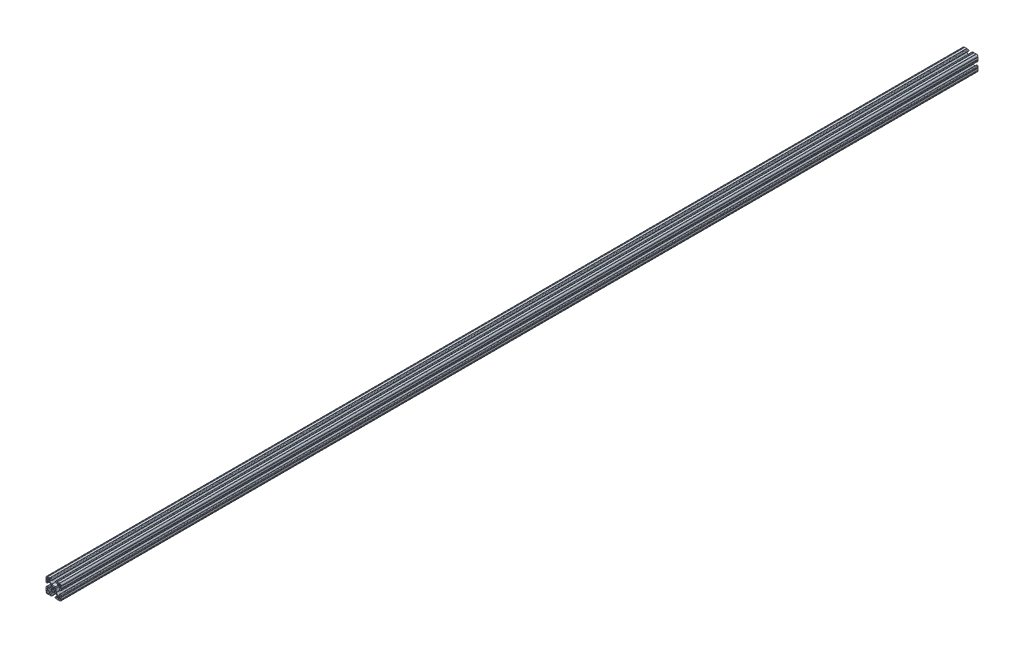
SolidWorks part; units mm, degrees
ref_plane "Front Plane" through (0, 0, 0) normal (0, 0, 1) x (1, 0, 0)
ref_plane "Top Plane" through (0, 0, 0) normal (0, 1, 0) x (1, 0, 0)
ref_plane "Right Plane" through (0, 0, 0) normal (1, 0, 0) x (0, 0, -1)
ref_plane "Plane1" through (0, 0, -2322.576) normal (0, 0, -1) x (-1, 0, 0)
sketch "Sketch1" plane through (0, 0, -2322.576) normal (0, 0, -1) x (-1, 0, 0)
  line L0 (17.2466, 14.4526) -> (17.2466, 12.2428)
  line L1 (16.8656, 11.8618) -> (15.0927, 11.8618)
  line L2 (15.0927, 11.8618) -> (14.5542, 12.4003)
  line L3 (14.5542, 12.4003) -> (14.0157, 11.8618)
  line L4 (14.0157, 11.8618) -> (12.2428, 11.8618)
  line L5 (11.8618, 12.2428) -> (11.8618, 14.0157)
  line L6 (11.8618, 14.0157) -> (12.4003, 14.5542)
  line L7 (12.4003, 14.5542) -> (11.8618, 15.0927)
  line L8 (11.8618, 15.0927) -> (11.8618, 16.8656)
  line L9 (12.2428, 17.2466) -> (14.4526, 17.2466)
  line L10 (17.2466, -12.2428) -> (17.2466, -14.4526)
  line L11 (14.4526, -17.2466) -> (12.2428, -17.2466)
  line L12 (11.8618, -16.8656) -> (11.8618, -15.0927)
  line L13 (11.8618, -15.0927) -> (12.4003, -14.5542)
  line L14 (12.4003, -14.5542) -> (11.8618, -14.0157)
  line L15 (11.8618, -14.0157) -> (11.8618, -12.2428)
  line L16 (12.2428, -11.8618) -> (14.0157, -11.8618)
  line L17 (14.0157, -11.8618) -> (14.5542, -12.4003)
  line L18 (14.5542, -12.4003) -> (15.0927, -11.8618)
  line L19 (15.0927, -11.8618) -> (16.8656, -11.8618)
  line L20 (5.1689, -3.9207) -> (5.1689, -4.9149)
  line L21 (4.9149, -5.1689) -> (3.9207, -5.1689)
  line L22 (3.2921, -4.9085) -> (1.5823, -3.1988)
  line L23 (-1.5823, -3.1988) -> (-3.2921, -4.9085)
  line L24 (-3.9207, -5.1689) -> (-4.9149, -5.1689)
  line L25 (-5.1689, -4.9149) -> (-5.1689, -3.9207)
  line L26 (-4.9085, -3.2921) -> (-3.1988, -1.5823)
  line L27 (-3.1988, 1.5823) -> (-4.9085, 3.2921)
  line L28 (-5.1689, 3.9207) -> (-5.1689, 4.9149)
  line L29 (-4.9149, 5.1689) -> (-3.9207, 5.1689)
  line L30 (-3.2921, 4.9085) -> (-1.5823, 3.1988)
  line L31 (1.5823, 3.1988) -> (3.2921, 4.9085)
  line L32 (3.9207, 5.1689) -> (4.9149, 5.1689)
  line L33 (5.1689, 4.9149) -> (5.1689, 3.9207)
  line L34 (4.9085, 3.2921) -> (3.1988, 1.5823)
  line L35 (3.1988, -1.5823) -> (4.9085, -3.2921)
  line L36 (-11.8618, -12.2428) -> (-11.8618, -14.0157)
  line L37 (-11.8618, -14.0157) -> (-12.4003, -14.5542)
  line L38 (-12.4003, -14.5542) -> (-11.8618, -15.0927)
  line L39 (-11.8618, -15.0927) -> (-11.8618, -16.8656)
  line L40 (-12.2428, -17.2466) -> (-14.4526, -17.2466)
  line L41 (-17.2466, -14.4526) -> (-17.2466, -12.2428)
  line L42 (-16.8656, -11.8618) -> (-15.0927, -11.8618)
  line L43 (-15.0927, -11.8618) -> (-14.5542, -12.4003)
  line L44 (-14.5542, -12.4003) -> (-14.0157, -11.8618)
  line L45 (-14.0157, -11.8618) -> (-12.2428, -11.8618)
  line L46 (-11.8618, 16.8656) -> (-11.8618, 15.0927)
  line L47 (-11.8618, 15.0927) -> (-12.4003, 14.5542)
  line L48 (-12.4003, 14.5542) -> (-11.8618, 14.0157)
  line L49 (-11.8618, 14.0157) -> (-11.8618, 12.2428)
  line L50 (-12.2428, 11.8618) -> (-14.0157, 11.8618)
  line L51 (-14.0157, 11.8618) -> (-14.5542, 12.4003)
  line L52 (-14.5542, 12.4003) -> (-15.0927, 11.8618)
  line L53 (-15.0927, 11.8618) -> (-16.8656, 11.8618)
  line L54 (-17.2466, 12.2428) -> (-17.2466, 14.4526)
  line L55 (-14.4526, 17.2466) -> (-12.2428, 17.2466)
  line L56 (19.05, -14.3256) -> (19.05, -9.4996)
  line L57 (19.05, -7.9756) -> (19.05, -5.6388)
  line L58 (17.4752, -4.064) -> (16.5608, -4.064)
  line L59 (14.986, -5.6388) -> (14.986, -6.35)
  line L60 (15.367, -6.731) -> (15.6972, -6.731)
  line L61 (16.0782, -7.112) -> (16.0782, -9.398)
  line L62 (15.1892, -10.287) -> (12.3756, -10.287)
  line L63 (11.4776, -9.915) -> (7.1157, -5.5531)
  line L64 (6.7437, -4.6551) -> (6.7437, 4.6551)
  line L65 (7.1157, 5.5531) -> (11.4776, 9.915)
  line L66 (12.3756, 10.287) -> (15.1892, 10.287)
  line L67 (16.0782, 9.398) -> (16.0782, 7.112)
  line L68 (15.6972, 6.731) -> (15.367, 6.731)
  line L69 (14.986, 6.35) -> (14.986, 5.6388)
  line L70 (16.5608, 4.064) -> (17.4752, 4.064)
  line L71 (19.05, 5.6388) -> (19.05, 7.9756)
  line L72 (19.05, 9.4996) -> (19.05, 14.3256)
  line L73 (14.3256, 19.05) -> (9.4996, 19.05)
  line L74 (7.9756, 19.05) -> (5.6388, 19.05)
  line L75 (4.064, 17.4752) -> (4.064, 16.5608)
  line L76 (5.6388, 14.986) -> (6.35, 14.986)
  line L77 (6.731, 15.367) -> (6.731, 15.6972)
  line L78 (7.112, 16.0782) -> (9.398, 16.0782)
  line L79 (10.287, 15.1892) -> (10.287, 12.3756)
  line L80 (9.915, 11.4776) -> (5.5531, 7.1157)
  line L81 (4.6551, 6.7437) -> (-4.6551, 6.7437)
  line L82 (-5.5531, 7.1157) -> (-9.915, 11.4776)
  line L83 (-10.287, 12.3756) -> (-10.287, 15.1892)
  line L84 (-9.398, 16.0782) -> (-7.112, 16.0782)
  line L85 (-6.731, 15.6972) -> (-6.731, 15.367)
  line L86 (-6.35, 14.986) -> (-5.6388, 14.986)
  line L87 (-4.064, 16.5608) -> (-4.064, 17.4752)
  line L88 (-5.6388, 19.05) -> (-7.9756, 19.05)
  line L89 (-9.4996, 19.05) -> (-14.3256, 19.05)
  line L90 (-19.05, 14.3256) -> (-19.05, 9.4996)
  line L91 (-19.05, 7.9756) -> (-19.05, 5.6388)
  line L92 (-17.4752, 4.064) -> (-16.5608, 4.064)
  line L93 (-14.986, 5.6388) -> (-14.986, 6.35)
  line L94 (-15.367, 6.731) -> (-15.6972, 6.731)
  line L95 (-16.0782, 7.112) -> (-16.0782, 9.398)
  line L96 (-15.1892, 10.287) -> (-12.3756, 10.287)
  line L97 (-11.4776, 9.915) -> (-7.1157, 5.5531)
  line L98 (-6.7437, 4.6551) -> (-6.7437, -4.6551)
  line L99 (-7.1157, -5.5531) -> (-11.4776, -9.915)
  line L100 (-12.3756, -10.287) -> (-15.1892, -10.287)
  line L101 (-16.0782, -9.398) -> (-16.0782, -7.112)
  line L102 (-15.6972, -6.731) -> (-15.367, -6.731)
  line L103 (-14.986, -6.35) -> (-14.986, -5.6388)
  line L104 (-16.5608, -4.064) -> (-17.4752, -4.064)
  line L105 (-19.05, -5.6388) -> (-19.05, -7.9756)
  line L106 (-19.05, -9.4996) -> (-19.05, -14.3256)
  line L107 (-14.3256, -19.05) -> (-9.4996, -19.05)
  line L108 (-7.9756, -19.05) -> (-5.6388, -19.05)
  line L109 (-4.064, -17.4752) -> (-4.064, -16.5608)
  line L110 (-5.6388, -14.986) -> (-6.35, -14.986)
  line L111 (-6.731, -15.367) -> (-6.731, -15.6972)
  line L112 (-7.112, -16.0782) -> (-9.398, -16.0782)
  line L113 (-10.287, -15.1892) -> (-10.287, -12.3756)
  line L114 (-9.915, -11.4776) -> (-5.5531, -7.1157)
  line L115 (-4.6551, -6.7437) -> (4.6551, -6.7437)
  line L116 (5.5531, -7.1157) -> (9.915, -11.4776)
  line L117 (10.287, -12.3756) -> (10.287, -15.1892)
  line L118 (9.398, -16.0782) -> (7.112, -16.0782)
  line L119 (6.731, -15.6972) -> (6.731, -15.367)
  line L120 (6.35, -14.986) -> (5.6388, -14.986)
  line L121 (4.064, -16.5608) -> (4.064, -17.4752)
  line L122 (5.6388, -19.05) -> (7.9756, -19.05)
  line L123 (9.4996, -19.05) -> (14.3256, -19.05)
  arc A0 (17.2466, 12.2428) -> (16.8656, 11.8618) centre (16.8656, 12.2428) cw
  arc A1 (12.2428, 11.8618) -> (11.8618, 12.2428) centre (12.2428, 12.2428) cw
  arc A2 (11.8618, 16.8656) -> (12.2428, 17.2466) centre (12.2428, 16.8656) cw
  arc A3 (14.4526, 17.2466) -> (17.2466, 14.4526) centre (14.4526, 14.4526) cw
  arc A4 (17.2466, -14.4526) -> (14.4526, -17.2466) centre (14.4526, -14.4526) cw
  arc A5 (12.2428, -17.2466) -> (11.8618, -16.8656) centre (12.2428, -16.8656) cw
  arc A6 (11.8618, -12.2428) -> (12.2428, -11.8618) centre (12.2428, -12.2428) cw
  arc A7 (16.8656, -11.8618) -> (17.2466, -12.2428) centre (16.8656, -12.2428) cw
  arc A8 (5.1689, -4.9149) -> (4.9149, -5.1689) centre (4.9149, -4.9149) cw
  arc A9 (3.9207, -5.1689) -> (3.2921, -4.9085) centre (3.9207, -4.2799) cw
  arc A10 (1.5823, -3.1988) -> (1.178, -3.1119) centre (1.3129, -3.4682) ccw
  arc A11 (1.178, -3.1119) -> (-1.178, -3.1119) centre (0, 0) cw
  arc A12 (-1.178, -3.1119) -> (-1.5823, -3.1988) centre (-1.3129, -3.4682) ccw
  arc A13 (-3.2921, -4.9085) -> (-3.9207, -5.1689) centre (-3.9207, -4.2799) cw
  arc A14 (-4.9149, -5.1689) -> (-5.1689, -4.9149) centre (-4.9149, -4.9149) cw
  arc A15 (-5.1689, -3.9207) -> (-4.9085, -3.2921) centre (-4.2799, -3.9207) cw
  arc A16 (-3.1988, -1.5823) -> (-3.1119, -1.178) centre (-3.4682, -1.3129) ccw
  arc A17 (-3.1119, -1.178) -> (-3.1119, 1.178) centre (0, 0) cw
  arc A18 (-3.1119, 1.178) -> (-3.1988, 1.5823) centre (-3.4682, 1.3129) ccw
  arc A19 (-4.9085, 3.2921) -> (-5.1689, 3.9207) centre (-4.2799, 3.9207) cw
  arc A20 (-5.1689, 4.9149) -> (-4.9149, 5.1689) centre (-4.9149, 4.9149) cw
  arc A21 (-3.9207, 5.1689) -> (-3.2921, 4.9085) centre (-3.9207, 4.2799) cw
  arc A22 (-1.5823, 3.1988) -> (-1.178, 3.1119) centre (-1.3129, 3.4682) ccw
  arc A23 (-1.178, 3.1119) -> (1.178, 3.1119) centre (0, 0) cw
  arc A24 (1.178, 3.1119) -> (1.5823, 3.1988) centre (1.3129, 3.4682) ccw
  arc A25 (3.2921, 4.9085) -> (3.9207, 5.1689) centre (3.9207, 4.2799) cw
  arc A26 (4.9149, 5.1689) -> (5.1689, 4.9149) centre (4.9149, 4.9149) cw
  arc A27 (5.1689, 3.9207) -> (4.9085, 3.2921) centre (4.2799, 3.9207) cw
  arc A28 (3.1988, 1.5823) -> (3.1119, 1.178) centre (3.4682, 1.3129) ccw
  arc A29 (3.1119, 1.178) -> (3.1119, -1.178) centre (0, 0) cw
  arc A30 (3.1119, -1.178) -> (3.1988, -1.5823) centre (3.4682, -1.3129) ccw
  arc A31 (4.9085, -3.2921) -> (5.1689, -3.9207) centre (4.2799, -3.9207) cw
  arc A32 (-11.8618, -16.8656) -> (-12.2428, -17.2466) centre (-12.2428, -16.8656) cw
  arc A33 (-14.4526, -17.2466) -> (-17.2466, -14.4526) centre (-14.4526, -14.4526) cw
  arc A34 (-17.2466, -12.2428) -> (-16.8656, -11.8618) centre (-16.8656, -12.2428) cw
  arc A35 (-12.2428, -11.8618) -> (-11.8618, -12.2428) centre (-12.2428, -12.2428) cw
  arc A36 (-12.2428, 17.2466) -> (-11.8618, 16.8656) centre (-12.2428, 16.8656) cw
  arc A37 (-11.8618, 12.2428) -> (-12.2428, 11.8618) centre (-12.2428, 12.2428) cw
  arc A38 (-16.8656, 11.8618) -> (-17.2466, 12.2428) centre (-16.8656, 12.2428) cw
  arc A39 (-17.2466, 14.4526) -> (-14.4526, 17.2466) centre (-14.4526, 14.4526) cw
  arc A40 (19.05, -9.4996) -> (19.05, -7.9756) centre (19.05, -8.7376) cw
  arc A41 (19.05, -5.6388) -> (17.4752, -4.064) centre (17.4752, -5.6388) ccw
  arc A42 (16.5608, -4.064) -> (14.986, -5.6388) centre (16.5608, -5.6388) ccw
  arc A43 (14.986, -6.35) -> (15.367, -6.731) centre (15.367, -6.35) ccw
  arc A44 (15.6972, -6.731) -> (16.0782, -7.112) centre (15.6972, -7.112) cw
  arc A45 (16.0782, -9.398) -> (15.1892, -10.287) centre (15.1892, -9.398) cw
  arc A46 (12.3756, -10.287) -> (11.4776, -9.915) centre (12.3756, -9.017) cw
  arc A47 (7.1157, -5.5531) -> (6.7437, -4.6551) centre (8.0137, -4.6551) cw
  arc A48 (6.7437, 4.6551) -> (7.1157, 5.5531) centre (8.0137, 4.6551) cw
  arc A49 (11.4776, 9.915) -> (12.3756, 10.287) centre (12.3756, 9.017) cw
  arc A50 (15.1892, 10.287) -> (16.0782, 9.398) centre (15.1892, 9.398) cw
  arc A51 (16.0782, 7.112) -> (15.6972, 6.731) centre (15.6972, 7.112) cw
  arc A52 (15.367, 6.731) -> (14.986, 6.35) centre (15.367, 6.35) ccw
  arc A53 (14.986, 5.6388) -> (16.5608, 4.064) centre (16.5608, 5.6388) ccw
  arc A54 (17.4752, 4.064) -> (19.05, 5.6388) centre (17.4752, 5.6388) ccw
  arc A55 (19.05, 7.9756) -> (19.05, 9.4996) centre (19.05, 8.7376) cw
  arc A56 (19.05, 14.3256) -> (19.0499, 15.8496) centre (19.05, 15.0876) cw
  arc A57 (19.0499, 15.8496) -> (15.8496, 19.0499) centre (15.875, 15.875) ccw
  arc A58 (15.8496, 19.0499) -> (14.3256, 19.05) centre (15.0876, 19.05) cw
  arc A59 (9.4996, 19.05) -> (7.9756, 19.05) centre (8.7376, 19.05) cw
  arc A60 (5.6388, 19.05) -> (4.064, 17.4752) centre (5.6388, 17.4752) ccw
  arc A61 (4.064, 16.5608) -> (5.6388, 14.986) centre (5.6388, 16.5608) ccw
  arc A62 (6.35, 14.986) -> (6.731, 15.367) centre (6.35, 15.367) ccw
  arc A63 (6.731, 15.6972) -> (7.112, 16.0782) centre (7.112, 15.6972) cw
  arc A64 (9.398, 16.0782) -> (10.287, 15.1892) centre (9.398, 15.1892) cw
  arc A65 (10.287, 12.3756) -> (9.915, 11.4776) centre (9.017, 12.3756) cw
  arc A66 (5.5531, 7.1157) -> (4.6551, 6.7437) centre (4.6551, 8.0137) cw
  arc A67 (-4.6551, 6.7437) -> (-5.5531, 7.1157) centre (-4.6551, 8.0137) cw
  arc A68 (-9.915, 11.4776) -> (-10.287, 12.3756) centre (-9.017, 12.3756) cw
  arc A69 (-10.287, 15.1892) -> (-9.398, 16.0782) centre (-9.398, 15.1892) cw
  arc A70 (-7.112, 16.0782) -> (-6.731, 15.6972) centre (-7.112, 15.6972) cw
  arc A71 (-6.731, 15.367) -> (-6.35, 14.986) centre (-6.35, 15.367) ccw
  arc A72 (-5.6388, 14.986) -> (-4.064, 16.5608) centre (-5.6388, 16.5608) ccw
  arc A73 (-4.064, 17.4752) -> (-5.6388, 19.05) centre (-5.6388, 17.4752) ccw
  arc A74 (-7.9756, 19.05) -> (-9.4996, 19.05) centre (-8.7376, 19.05) cw
  arc A75 (-14.3256, 19.05) -> (-15.8496, 19.0499) centre (-15.0876, 19.05) cw
  arc A76 (-15.8496, 19.0499) -> (-19.0499, 15.8496) centre (-15.875, 15.875) ccw
  arc A77 (-19.0499, 15.8496) -> (-19.05, 14.3256) centre (-19.05, 15.0876) cw
  arc A78 (-19.05, 9.4996) -> (-19.05, 7.9756) centre (-19.05, 8.7376) cw
  arc A79 (-19.05, 5.6388) -> (-17.4752, 4.064) centre (-17.4752, 5.6388) ccw
  arc A80 (-16.5608, 4.064) -> (-14.986, 5.6388) centre (-16.5608, 5.6388) ccw
  arc A81 (-14.986, 6.35) -> (-15.367, 6.731) centre (-15.367, 6.35) ccw
  arc A82 (-15.6972, 6.731) -> (-16.0782, 7.112) centre (-15.6972, 7.112) cw
  arc A83 (-16.0782, 9.398) -> (-15.1892, 10.287) centre (-15.1892, 9.398) cw
  arc A84 (-12.3756, 10.287) -> (-11.4776, 9.915) centre (-12.3756, 9.017) cw
  arc A85 (-7.1157, 5.5531) -> (-6.7437, 4.6551) centre (-8.0137, 4.6551) cw
  arc A86 (-6.7437, -4.6551) -> (-7.1157, -5.5531) centre (-8.0137, -4.6551) cw
  arc A87 (-11.4776, -9.915) -> (-12.3756, -10.287) centre (-12.3756, -9.017) cw
  arc A88 (-15.1892, -10.287) -> (-16.0782, -9.398) centre (-15.1892, -9.398) cw
  arc A89 (-16.0782, -7.112) -> (-15.6972, -6.731) centre (-15.6972, -7.112) cw
  arc A90 (-15.367, -6.731) -> (-14.986, -6.35) centre (-15.367, -6.35) ccw
  arc A91 (-14.986, -5.6388) -> (-16.5608, -4.064) centre (-16.5608, -5.6388) ccw
  arc A92 (-17.4752, -4.064) -> (-19.05, -5.6388) centre (-17.4752, -5.6388) ccw
  arc A93 (-19.05, -7.9756) -> (-19.05, -9.4996) centre (-19.05, -8.7376) cw
  arc A94 (-19.05, -14.3256) -> (-19.0499, -15.8496) centre (-19.05, -15.0876) cw
  arc A95 (-19.0499, -15.8496) -> (-15.8496, -19.0499) centre (-15.875, -15.875) ccw
  arc A96 (-15.8496, -19.0499) -> (-14.3256, -19.05) centre (-15.0876, -19.05) cw
  arc A97 (-9.4996, -19.05) -> (-7.9756, -19.05) centre (-8.7376, -19.05) cw
  arc A98 (-5.6388, -19.05) -> (-4.064, -17.4752) centre (-5.6388, -17.4752) ccw
  arc A99 (-4.064, -16.5608) -> (-5.6388, -14.986) centre (-5.6388, -16.5608) ccw
  arc A100 (-6.35, -14.986) -> (-6.731, -15.367) centre (-6.35, -15.367) ccw
  arc A101 (-6.731, -15.6972) -> (-7.112, -16.0782) centre (-7.112, -15.6972) cw
  arc A102 (-9.398, -16.0782) -> (-10.287, -15.1892) centre (-9.398, -15.1892) cw
  arc A103 (-10.287, -12.3756) -> (-9.915, -11.4776) centre (-9.017, -12.3756) cw
  arc A104 (-5.5531, -7.1157) -> (-4.6551, -6.7437) centre (-4.6551, -8.0137) cw
  arc A105 (4.6551, -6.7437) -> (5.5531, -7.1157) centre (4.6551, -8.0137) cw
  arc A106 (9.915, -11.4776) -> (10.287, -12.3756) centre (9.017, -12.3756) cw
  arc A107 (10.287, -15.1892) -> (9.398, -16.0782) centre (9.398, -15.1892) cw
  arc A108 (7.112, -16.0782) -> (6.731, -15.6972) centre (7.112, -15.6972) cw
  arc A109 (6.731, -15.367) -> (6.35, -14.986) centre (6.35, -15.367) ccw
  arc A110 (5.6388, -14.986) -> (4.064, -16.5608) centre (5.6388, -16.5608) ccw
  arc A111 (4.064, -17.4752) -> (5.6388, -19.05) centre (5.6388, -17.4752) ccw
  arc A112 (7.9756, -19.05) -> (9.4996, -19.05) centre (8.7376, -19.05) cw
  arc A113 (14.3256, -19.05) -> (15.8496, -19.0499) centre (15.0876, -19.05) cw
  arc A114 (15.8496, -19.0499) -> (19.0499, -15.8496) centre (15.875, -15.875) ccw
  arc A115 (19.0499, -15.8496) -> (19.05, -14.3256) centre (19.05, -15.0876) cw
extrude "Boss-Extrude1" add sketch "Sketch1" against normal blind 2322.576
